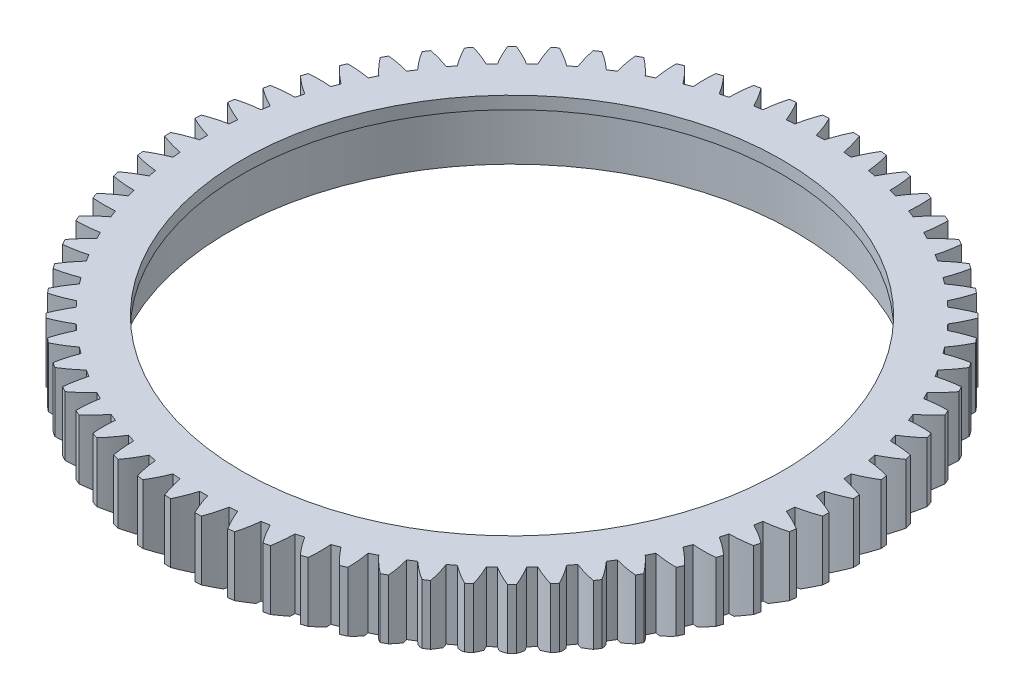
SolidWorks part; units mm, degrees
ref_plane "Front Plane" through (0, 0, 0) normal (0, 0, 1) x (1, 0, 0)
ref_plane "Top Plane" through (0, 0, 0) normal (0, 1, 0) x (1, 0, 0)
ref_plane "Right Plane" through (0, 0, 0) normal (1, 0, 0) x (0, 0, -1)
sketch "Sketch1" plane through (0, 0, 0) normal (0, 1, 0) x (1, 0, 0)
  circle A0 centre (0, 0) radius 53
  circle A1 centre (0, 0) radius 43
  dimension "D1" = 106
  dimension "D2" = 86
extrude "Boss-Extrude1" add sketch "Sketch1" along normal blind 11
sketch "Sketch3" plane through (0, 0, 0) normal (0, -1, 0) x (1, 0, 0)
  circle A0 centre (0, 0) radius 45.1
  dimension "D1" = 90.2
extrude "Cut-Extrude2" cut sketch "Sketch3" against normal blind 9
sketch "Sketch4" plane through (0, 0, 0) normal (0, -1, 0) x (1, 0, 0)
  arc A0 (-52.4646, 1.9286) -> (-49.1199, 0.6319) centre (-43.4466, 20.2271) ccw
  arc A1 (-49.1199, 0.6319) -> (-49.1199, -0.6319) centre (0, 0) ccw
  arc A2 (-49.1199, -0.6319) -> (-52.4646, -1.9286) centre (-43.4466, -20.2271) ccw
  arc A3 (-52.4646, -1.9286) -> (-52.4187, -2.9204) centre (0, 0) ccw
  arc A4 (-52.4187, -2.9204) -> (-48.9687, -3.903) centre (-45.1276, 16.1321) ccw
  arc A5 (-48.9687, -3.903) -> (-48.8521, -5.1614) centre (0, 0) ccw
  arc A6 (-48.8521, -5.1614) -> (-52.0628, -6.7612) centre (-41.3949, -24.1496) ccw
  arc A7 (-52.0628, -6.7612) -> (-51.9256, -7.7446) centre (0, 0) ccw
  arc A8 (-51.9256, -7.7446) -> (-48.3997, -8.4046) centre (-46.4235, 11.8994) ccw
  arc A9 (-48.3997, -8.4046) -> (-48.1675, -9.6469) centre (0, 0) ccw
  arc A10 (-48.1675, -9.6469) -> (-51.2169, -11.5361) centre (-38.9901, -27.866) ccw
  arc A11 (-51.2169, -11.5361) -> (-50.9896, -12.5026) centre (0, 0) ccw
  arc A12 (-50.9896, -12.5026) -> (-47.4177, -12.8345) centre (-47.3234, 7.5653) ccw
  arc A13 (-47.4177, -12.8345) -> (-47.0719, -14.0501) centre (0, 0) ccw
  arc A14 (-47.0719, -14.0501) -> (-49.934, -16.2126) centre (-36.2526, -31.3447) ccw
  arc A15 (-49.934, -16.2126) -> (-49.6184, -17.154) centre (0, 0) ccw
  arc A16 (-49.6184, -17.154) -> (-46.0312, -17.1549) centre (-47.8196, 3.1665) ccw
  arc A17 (-46.0312, -17.1549) -> (-45.5747, -18.3334) centre (0, 0) ccw
  arc A18 (-45.5747, -18.3334) -> (-48.2251, -20.7508) centre (-33.2058, -34.5559) ccw
  arc A19 (-48.2251, -20.7508) -> (-47.824, -21.659) centre (0, 0) ccw
  arc A20 (-47.824, -21.659) -> (-44.252, -21.329) centre (-47.9078, -1.2592) ccw
  arc A21 (-44.252, -21.329) -> (-43.6887, -22.4603) centre (0, 0) ccw
  arc A22 (-43.6887, -22.4603) -> (-46.1047, -25.1119) centre (-29.8758, -37.4724) ccw
  arc A23 (-46.1047, -25.1119) -> (-45.6216, -25.9793) centre (0, 0) ccw
  arc A24 (-45.6216, -25.9793) -> (-42.0953, -25.3211) centre (-47.5872, -5.6742) ccw
  arc A25 (-42.0953, -25.3211) -> (-41.43, -26.3956) centre (0, 0) ccw
  arc A26 (-41.43, -26.3956) -> (-43.591, -29.2588) centre (-26.2908, -40.0691) ccw
  arc A27 (-43.591, -29.2588) -> (-43.0299, -30.0779) centre (0, 0) ccw
  arc A28 (-43.0299, -30.0779) -> (-39.5794, -29.0971) centre (-46.8607, -10.0408) ccw
  arc A29 (-39.5794, -29.0971) -> (-38.8178, -30.1056) centre (0, 0) ccw
  arc A30 (-38.8178, -30.1056) -> (-40.7054, -33.156) centre (-22.4815, -42.324) ccw
  arc A31 (-40.7054, -33.156) -> (-40.0711, -33.9199) centre (0, 0) ccw
  arc A32 (-40.0711, -33.9199) -> (-36.7258, -32.6249) centre (-45.7343, -14.3217) ccw
  arc A33 (-36.7258, -32.6249) -> (-35.8744, -33.5589) centre (0, 0) ccw
  arc A34 (-35.8744, -33.5589) -> (-37.4725, -36.7704) centre (-18.4805, -44.2178) ccw
  arc A35 (-37.4725, -36.7704) -> (-36.7704, -37.4725) centre (0, 0) ccw
  arc A36 (-36.7704, -37.4725) -> (-33.5589, -35.8744) centre (-44.2178, -18.4805) ccw
  arc A37 (-33.5589, -35.8744) -> (-32.6249, -36.7258) centre (0, 0) ccw
  arc A38 (-32.6249, -36.7258) -> (-33.9199, -40.0711) centre (-14.3217, -45.7343) ccw
  arc A39 (-33.9199, -40.0711) -> (-33.156, -40.7054) centre (0, 0) ccw
  arc A40 (-33.156, -40.7054) -> (-30.1056, -38.8178) centre (-42.324, -22.4815) ccw
  arc A41 (-30.1056, -38.8178) -> (-29.0971, -39.5794) centre (0, 0) ccw
  arc A42 (-29.0971, -39.5794) -> (-30.0779, -43.0299) centre (-10.0408, -46.8607) ccw
  arc A43 (-30.0779, -43.0299) -> (-29.2588, -43.591) centre (0, 0) ccw
  arc A44 (-29.2588, -43.591) -> (-26.3956, -41.43) centre (-40.0691, -26.2908) ccw
  arc A45 (-26.3956, -41.43) -> (-25.3211, -42.0953) centre (0, 0) ccw
  arc A46 (-25.3211, -42.0953) -> (-25.9793, -45.6216) centre (-5.6742, -47.5872) ccw
  arc A47 (-25.9793, -45.6216) -> (-25.1119, -46.1047) centre (0, 0) ccw
  arc A48 (-25.1119, -46.1047) -> (-22.4603, -43.6887) centre (-37.4724, -29.8758) ccw
  arc A49 (-22.4603, -43.6887) -> (-21.329, -44.252) centre (0, 0) ccw
  arc A50 (-21.329, -44.252) -> (-21.659, -47.824) centre (-1.2592, -47.9078) ccw
  arc A51 (-21.659, -47.824) -> (-20.7508, -48.2251) centre (0, 0) ccw
  arc A52 (-20.7508, -48.2251) -> (-18.3334, -45.5747) centre (-34.5559, -33.2058) ccw
  arc A53 (-18.3334, -45.5747) -> (-17.1549, -46.0312) centre (0, 0) ccw
  arc A54 (-17.1549, -46.0312) -> (-17.154, -49.6184) centre (3.1665, -47.8196) ccw
  arc A55 (-17.154, -49.6184) -> (-16.2126, -49.934) centre (0, 0) ccw
  arc A56 (-16.2126, -49.934) -> (-14.0501, -47.0719) centre (-31.3447, -36.2526) ccw
  arc A57 (-14.0501, -47.0719) -> (-12.8345, -47.4177) centre (0, 0) ccw
  arc A58 (-12.8345, -47.4177) -> (-12.5026, -50.9896) centre (7.5653, -47.3234) ccw
  arc A59 (-12.5026, -50.9896) -> (-11.5361, -51.2169) centre (0, 0) ccw
  arc A60 (-11.5361, -51.2169) -> (-9.6469, -48.1675) centre (-27.866, -38.9901) ccw
  arc A61 (-9.6469, -48.1675) -> (-8.4046, -48.3997) centre (0, 0) ccw
  arc A62 (-8.4046, -48.3997) -> (-7.7446, -51.9256) centre (11.8994, -46.4235) ccw
  arc A63 (-7.7446, -51.9256) -> (-6.7612, -52.0628) centre (0, 0) ccw
  arc A64 (-6.7612, -52.0628) -> (-5.1614, -48.8521) centre (-24.1496, -41.3949) ccw
  arc A65 (-5.1614, -48.8521) -> (-3.903, -48.9687) centre (0, 0) ccw
  arc A66 (-3.903, -48.9687) -> (-2.9204, -52.4187) centre (16.1321, -45.1276) ccw
  arc A67 (-2.9204, -52.4187) -> (-1.9286, -52.4646) centre (0, 0) ccw
  arc A68 (-1.9286, -52.4646) -> (-0.6319, -49.1199) centre (-20.2271, -43.4466) ccw
  arc A69 (-0.6319, -49.1199) -> (0.6319, -49.1199) centre (0, 0) ccw
  arc A70 (0.6319, -49.1199) -> (1.9286, -52.4646) centre (20.2271, -43.4466) ccw
  arc A71 (1.9286, -52.4646) -> (2.9204, -52.4187) centre (0, 0) ccw
  arc A72 (2.9204, -52.4187) -> (3.903, -48.9687) centre (-16.1321, -45.1276) ccw
  arc A73 (3.903, -48.9687) -> (5.1614, -48.8521) centre (0, 0) ccw
  arc A74 (5.1614, -48.8521) -> (6.7612, -52.0628) centre (24.1496, -41.3949) ccw
  arc A75 (6.7612, -52.0628) -> (7.7446, -51.9256) centre (0, 0) ccw
  arc A76 (7.7446, -51.9256) -> (8.4046, -48.3997) centre (-11.8994, -46.4235) ccw
  arc A77 (8.4046, -48.3997) -> (9.6469, -48.1675) centre (0, 0) ccw
  arc A78 (9.6469, -48.1675) -> (11.5361, -51.2169) centre (27.866, -38.9901) ccw
  arc A79 (11.5361, -51.2169) -> (12.5026, -50.9896) centre (0, 0) ccw
  arc A80 (12.5026, -50.9896) -> (12.8345, -47.4177) centre (-7.5653, -47.3234) ccw
  arc A81 (12.8345, -47.4177) -> (14.0501, -47.0719) centre (0, 0) ccw
  arc A82 (14.0501, -47.0719) -> (16.2126, -49.934) centre (31.3447, -36.2526) ccw
  arc A83 (16.2126, -49.934) -> (17.154, -49.6184) centre (0, 0) ccw
  arc A84 (17.154, -49.6184) -> (17.1549, -46.0312) centre (-3.1665, -47.8196) ccw
  arc A85 (17.1549, -46.0312) -> (18.3334, -45.5747) centre (0, 0) ccw
  arc A86 (18.3334, -45.5747) -> (20.7508, -48.2251) centre (34.5559, -33.2058) ccw
  arc A87 (20.7508, -48.2251) -> (21.659, -47.824) centre (0, 0) ccw
  arc A88 (21.659, -47.824) -> (21.329, -44.252) centre (1.2592, -47.9078) ccw
  arc A89 (21.329, -44.252) -> (22.4603, -43.6887) centre (0, 0) ccw
  arc A90 (22.4603, -43.6887) -> (25.1119, -46.1047) centre (37.4724, -29.8758) ccw
  arc A91 (25.1119, -46.1047) -> (25.9793, -45.6216) centre (0, 0) ccw
  arc A92 (25.9793, -45.6216) -> (25.3211, -42.0953) centre (5.6742, -47.5872) ccw
  arc A93 (25.3211, -42.0953) -> (26.3956, -41.43) centre (0, 0) ccw
  arc A94 (26.3956, -41.43) -> (29.2588, -43.591) centre (40.0691, -26.2908) ccw
  arc A95 (29.2588, -43.591) -> (30.0779, -43.0299) centre (0, 0) ccw
  arc A96 (30.0779, -43.0299) -> (29.0971, -39.5794) centre (10.0408, -46.8607) ccw
  arc A97 (29.0971, -39.5794) -> (30.1056, -38.8178) centre (0, 0) ccw
  arc A98 (30.1056, -38.8178) -> (33.156, -40.7054) centre (42.324, -22.4815) ccw
  arc A99 (33.156, -40.7054) -> (33.9199, -40.0711) centre (0, 0) ccw
  arc A100 (33.9199, -40.0711) -> (32.6249, -36.7258) centre (14.3217, -45.7343) ccw
  arc A101 (32.6249, -36.7258) -> (33.5589, -35.8744) centre (0, 0) ccw
  arc A102 (33.5589, -35.8744) -> (36.7704, -37.4725) centre (44.2178, -18.4805) ccw
  arc A103 (36.7704, -37.4725) -> (37.4725, -36.7704) centre (0, 0) ccw
  arc A104 (37.4725, -36.7704) -> (35.8744, -33.5589) centre (18.4805, -44.2178) ccw
  arc A105 (35.8744, -33.5589) -> (36.7258, -32.6249) centre (0, 0) ccw
  arc A106 (36.7258, -32.6249) -> (40.0711, -33.9199) centre (45.7343, -14.3217) ccw
  arc A107 (40.0711, -33.9199) -> (40.7054, -33.156) centre (0, 0) ccw
  arc A108 (40.7054, -33.156) -> (38.8178, -30.1056) centre (22.4815, -42.324) ccw
  arc A109 (38.8178, -30.1056) -> (39.5794, -29.0971) centre (0, 0) ccw
  arc A110 (39.5794, -29.0971) -> (43.0299, -30.0779) centre (46.8607, -10.0408) ccw
  arc A111 (43.0299, -30.0779) -> (43.591, -29.2588) centre (0, 0) ccw
  arc A112 (43.591, -29.2588) -> (41.43, -26.3956) centre (26.2908, -40.0691) ccw
  arc A113 (41.43, -26.3956) -> (42.0953, -25.3211) centre (0, 0) ccw
  arc A114 (42.0953, -25.3211) -> (45.6216, -25.9793) centre (47.5872, -5.6742) ccw
  arc A115 (45.6216, -25.9793) -> (46.1047, -25.1119) centre (0, 0) ccw
  arc A116 (46.1047, -25.1119) -> (43.6887, -22.4603) centre (29.8758, -37.4724) ccw
  arc A117 (43.6887, -22.4603) -> (44.252, -21.329) centre (0, 0) ccw
  arc A118 (44.252, -21.329) -> (47.824, -21.659) centre (47.9078, -1.2592) ccw
  arc A119 (47.824, -21.659) -> (48.2251, -20.7508) centre (0, 0) ccw
  arc A120 (48.2251, -20.7508) -> (45.5747, -18.3334) centre (33.2058, -34.5559) ccw
  arc A121 (45.5747, -18.3334) -> (46.0312, -17.1549) centre (0, 0) ccw
  arc A122 (46.0312, -17.1549) -> (49.6184, -17.154) centre (47.8196, 3.1665) ccw
  arc A123 (49.6184, -17.154) -> (49.934, -16.2126) centre (0, 0) ccw
  arc A124 (49.934, -16.2126) -> (47.0719, -14.0501) centre (36.2526, -31.3447) ccw
  arc A125 (47.0719, -14.0501) -> (47.4177, -12.8345) centre (0, 0) ccw
  arc A126 (47.4177, -12.8345) -> (50.9896, -12.5026) centre (47.3234, 7.5653) ccw
  arc A127 (50.9896, -12.5026) -> (51.2169, -11.5361) centre (0, 0) ccw
  arc A128 (51.2169, -11.5361) -> (48.1675, -9.6469) centre (38.9901, -27.866) ccw
  arc A129 (48.1675, -9.6469) -> (48.3997, -8.4046) centre (0, 0) ccw
  arc A130 (48.3997, -8.4046) -> (51.9256, -7.7446) centre (46.4235, 11.8994) ccw
  arc A131 (51.9256, -7.7446) -> (52.0628, -6.7612) centre (0, 0) ccw
  arc A132 (52.0628, -6.7612) -> (48.8521, -5.1614) centre (41.3949, -24.1496) ccw
  arc A133 (48.8521, -5.1614) -> (48.9687, -3.903) centre (0, 0) ccw
  arc A134 (48.9687, -3.903) -> (52.4187, -2.9204) centre (45.1276, 16.1321) ccw
  arc A135 (52.4187, -2.9204) -> (52.4646, -1.9286) centre (0, 0) ccw
  arc A136 (52.4646, -1.9286) -> (49.1199, -0.6319) centre (43.4466, -20.2271) ccw
  arc A137 (49.1199, -0.6319) -> (49.1199, 0.6319) centre (0, 0) ccw
  arc A138 (49.1199, 0.6319) -> (52.4646, 1.9286) centre (43.4466, 20.2271) ccw
  arc A139 (52.4646, 1.9286) -> (52.4187, 2.9204) centre (0, 0) ccw
  arc A140 (52.4187, 2.9204) -> (48.9687, 3.903) centre (45.1276, -16.1321) ccw
  arc A141 (48.9687, 3.903) -> (48.8521, 5.1614) centre (0, 0) ccw
  arc A142 (48.8521, 5.1614) -> (52.0628, 6.7612) centre (41.3949, 24.1496) ccw
  arc A143 (52.0628, 6.7612) -> (51.9256, 7.7446) centre (0, 0) ccw
  arc A144 (51.9256, 7.7446) -> (48.3997, 8.4046) centre (46.4235, -11.8994) ccw
  arc A145 (48.3997, 8.4046) -> (48.1675, 9.6469) centre (0, 0) ccw
  arc A146 (48.1675, 9.6469) -> (51.2169, 11.5361) centre (38.9901, 27.866) ccw
  arc A147 (51.2169, 11.5361) -> (50.9896, 12.5026) centre (0, 0) ccw
  arc A148 (50.9896, 12.5026) -> (47.4177, 12.8345) centre (47.3234, -7.5653) ccw
  arc A149 (47.4177, 12.8345) -> (47.0719, 14.0501) centre (0, 0) ccw
  arc A150 (47.0719, 14.0501) -> (49.934, 16.2126) centre (36.2526, 31.3447) ccw
  arc A151 (49.934, 16.2126) -> (49.6184, 17.154) centre (0, 0) ccw
  arc A152 (49.6184, 17.154) -> (46.0312, 17.1549) centre (47.8196, -3.1665) ccw
  arc A153 (46.0312, 17.1549) -> (45.5747, 18.3334) centre (0, 0) ccw
  arc A154 (45.5747, 18.3334) -> (48.2251, 20.7508) centre (33.2058, 34.5559) ccw
  arc A155 (48.2251, 20.7508) -> (47.824, 21.659) centre (0, 0) ccw
  arc A156 (47.824, 21.659) -> (44.252, 21.329) centre (47.9078, 1.2592) ccw
  arc A157 (44.252, 21.329) -> (43.6887, 22.4603) centre (0, 0) ccw
  arc A158 (43.6887, 22.4603) -> (46.1047, 25.1119) centre (29.8758, 37.4724) ccw
  arc A159 (46.1047, 25.1119) -> (45.6216, 25.9793) centre (0, 0) ccw
  arc A160 (45.6216, 25.9793) -> (42.0953, 25.3211) centre (47.5872, 5.6742) ccw
  arc A161 (42.0953, 25.3211) -> (41.43, 26.3956) centre (0, 0) ccw
  arc A162 (41.43, 26.3956) -> (43.591, 29.2588) centre (26.2908, 40.0691) ccw
  arc A163 (43.591, 29.2588) -> (43.0299, 30.0779) centre (0, 0) ccw
  arc A164 (43.0299, 30.0779) -> (39.5794, 29.0971) centre (46.8607, 10.0408) ccw
  arc A165 (39.5794, 29.0971) -> (38.8178, 30.1056) centre (0, 0) ccw
  arc A166 (38.8178, 30.1056) -> (40.7054, 33.156) centre (22.4815, 42.324) ccw
  arc A167 (40.7054, 33.156) -> (40.0711, 33.9199) centre (0, 0) ccw
  arc A168 (40.0711, 33.9199) -> (36.7258, 32.6249) centre (45.7343, 14.3217) ccw
  arc A169 (36.7258, 32.6249) -> (35.8744, 33.5589) centre (0, 0) ccw
  arc A170 (35.8744, 33.5589) -> (37.4725, 36.7704) centre (18.4805, 44.2178) ccw
  arc A171 (37.4725, 36.7704) -> (36.7704, 37.4725) centre (0, 0) ccw
  arc A172 (36.7704, 37.4725) -> (33.5589, 35.8744) centre (44.2178, 18.4805) ccw
  arc A173 (33.5589, 35.8744) -> (32.6249, 36.7258) centre (0, 0) ccw
  arc A174 (32.6249, 36.7258) -> (33.9199, 40.0711) centre (14.3217, 45.7343) ccw
  arc A175 (33.9199, 40.0711) -> (33.156, 40.7054) centre (0, 0) ccw
  arc A176 (33.156, 40.7054) -> (30.1056, 38.8178) centre (42.324, 22.4815) ccw
  arc A177 (30.1056, 38.8178) -> (29.0971, 39.5794) centre (0, 0) ccw
  arc A178 (29.0971, 39.5794) -> (30.0779, 43.0299) centre (10.0408, 46.8607) ccw
  arc A179 (30.0779, 43.0299) -> (29.2588, 43.591) centre (0, 0) ccw
  arc A180 (29.2588, 43.591) -> (26.3956, 41.43) centre (40.0691, 26.2908) ccw
  arc A181 (26.3956, 41.43) -> (25.3211, 42.0953) centre (0, 0) ccw
  arc A182 (25.3211, 42.0953) -> (25.9793, 45.6216) centre (5.6742, 47.5872) ccw
  arc A183 (25.9793, 45.6216) -> (25.1119, 46.1047) centre (0, 0) ccw
  arc A184 (25.1119, 46.1047) -> (22.4603, 43.6887) centre (37.4724, 29.8758) ccw
  arc A185 (22.4603, 43.6887) -> (21.329, 44.252) centre (0, 0) ccw
  arc A186 (21.329, 44.252) -> (21.659, 47.824) centre (1.2592, 47.9078) ccw
  arc A187 (21.659, 47.824) -> (20.7508, 48.2251) centre (0, 0) ccw
  arc A188 (20.7508, 48.2251) -> (18.3334, 45.5747) centre (34.5559, 33.2058) ccw
  arc A189 (18.3334, 45.5747) -> (17.1549, 46.0312) centre (0, 0) ccw
  arc A190 (17.1549, 46.0312) -> (17.154, 49.6184) centre (-3.1665, 47.8196) ccw
  arc A191 (17.154, 49.6184) -> (16.2126, 49.934) centre (0, 0) ccw
  arc A192 (16.2126, 49.934) -> (14.0501, 47.0719) centre (31.3447, 36.2526) ccw
  arc A193 (14.0501, 47.0719) -> (12.8345, 47.4177) centre (0, 0) ccw
  arc A194 (12.8345, 47.4177) -> (12.5026, 50.9896) centre (-7.5653, 47.3234) ccw
  arc A195 (12.5026, 50.9896) -> (11.5361, 51.2169) centre (0, 0) ccw
  arc A196 (11.5361, 51.2169) -> (9.6469, 48.1675) centre (27.866, 38.9901) ccw
  arc A197 (9.6469, 48.1675) -> (8.4046, 48.3997) centre (0, 0) ccw
  arc A198 (8.4046, 48.3997) -> (7.7446, 51.9256) centre (-11.8994, 46.4235) ccw
  arc A199 (7.7446, 51.9256) -> (6.7612, 52.0628) centre (0, 0) ccw
  arc A200 (6.7612, 52.0628) -> (5.1614, 48.8521) centre (24.1496, 41.3949) ccw
  arc A201 (5.1614, 48.8521) -> (3.903, 48.9687) centre (0, 0) ccw
  arc A202 (3.903, 48.9687) -> (2.9204, 52.4187) centre (-16.1321, 45.1276) ccw
  arc A203 (2.9204, 52.4187) -> (1.9286, 52.4646) centre (0, 0) ccw
  arc A204 (1.9286, 52.4646) -> (0.6319, 49.1199) centre (20.2271, 43.4466) ccw
  arc A205 (0.6319, 49.1199) -> (-0.6319, 49.1199) centre (0, 0) ccw
  arc A206 (-0.6319, 49.1199) -> (-1.9286, 52.4646) centre (-20.2271, 43.4466) ccw
  arc A207 (-1.9286, 52.4646) -> (-2.9204, 52.4187) centre (0, 0) ccw
  arc A208 (-2.9204, 52.4187) -> (-3.903, 48.9687) centre (16.1321, 45.1276) ccw
  arc A209 (-3.903, 48.9687) -> (-5.1614, 48.8521) centre (0, 0) ccw
  arc A210 (-5.1614, 48.8521) -> (-6.7612, 52.0628) centre (-24.1496, 41.3949) ccw
  arc A211 (-6.7612, 52.0628) -> (-7.7446, 51.9256) centre (0, 0) ccw
  arc A212 (-7.7446, 51.9256) -> (-8.4046, 48.3997) centre (11.8994, 46.4235) ccw
  arc A213 (-8.4046, 48.3997) -> (-9.6469, 48.1675) centre (0, 0) ccw
  arc A214 (-9.6469, 48.1675) -> (-11.5361, 51.2169) centre (-27.866, 38.9901) ccw
  arc A215 (-11.5361, 51.2169) -> (-12.5026, 50.9896) centre (0, 0) ccw
  arc A216 (-12.5026, 50.9896) -> (-12.8345, 47.4177) centre (7.5653, 47.3234) ccw
  arc A217 (-12.8345, 47.4177) -> (-14.0501, 47.0719) centre (0, 0) ccw
  arc A218 (-14.0501, 47.0719) -> (-16.2126, 49.934) centre (-31.3447, 36.2526) ccw
  arc A219 (-16.2126, 49.934) -> (-17.154, 49.6184) centre (0, 0) ccw
  arc A220 (-17.154, 49.6184) -> (-17.1549, 46.0312) centre (3.1665, 47.8196) ccw
  arc A221 (-17.1549, 46.0312) -> (-18.3334, 45.5747) centre (0, 0) ccw
  arc A222 (-18.3334, 45.5747) -> (-20.7508, 48.2251) centre (-34.5559, 33.2058) ccw
  arc A223 (-20.7508, 48.2251) -> (-21.659, 47.824) centre (0, 0) ccw
  arc A224 (-21.659, 47.824) -> (-21.329, 44.252) centre (-1.2592, 47.9078) ccw
  arc A225 (-21.329, 44.252) -> (-22.4603, 43.6887) centre (0, 0) ccw
  arc A226 (-22.4603, 43.6887) -> (-25.1119, 46.1047) centre (-37.4724, 29.8758) ccw
  arc A227 (-25.1119, 46.1047) -> (-25.9793, 45.6216) centre (0, 0) ccw
  arc A228 (-25.9793, 45.6216) -> (-25.3211, 42.0953) centre (-5.6742, 47.5872) ccw
  arc A229 (-25.3211, 42.0953) -> (-26.3956, 41.43) centre (0, 0) ccw
  arc A230 (-26.3956, 41.43) -> (-29.2588, 43.591) centre (-40.0691, 26.2908) ccw
  arc A231 (-29.2588, 43.591) -> (-30.0779, 43.0299) centre (0, 0) ccw
  arc A232 (-30.0779, 43.0299) -> (-29.0971, 39.5794) centre (-10.0408, 46.8607) ccw
  arc A233 (-29.0971, 39.5794) -> (-30.1056, 38.8178) centre (0, 0) ccw
  arc A234 (-30.1056, 38.8178) -> (-33.156, 40.7054) centre (-42.324, 22.4815) ccw
  arc A235 (-33.156, 40.7054) -> (-33.9199, 40.0711) centre (0, 0) ccw
  arc A236 (-33.9199, 40.0711) -> (-32.6249, 36.7258) centre (-14.3217, 45.7343) ccw
  arc A237 (-32.6249, 36.7258) -> (-33.5589, 35.8744) centre (0, 0) ccw
  arc A238 (-33.5589, 35.8744) -> (-36.7704, 37.4725) centre (-44.2178, 18.4805) ccw
  arc A239 (-36.7704, 37.4725) -> (-37.4725, 36.7704) centre (0, 0) ccw
  arc A240 (-37.4725, 36.7704) -> (-35.8744, 33.5589) centre (-18.4805, 44.2178) ccw
  arc A241 (-35.8744, 33.5589) -> (-36.7258, 32.6249) centre (0, 0) ccw
  arc A242 (-36.7258, 32.6249) -> (-40.0711, 33.9199) centre (-45.7343, 14.3217) ccw
  arc A243 (-40.0711, 33.9199) -> (-40.7054, 33.156) centre (0, 0) ccw
  arc A244 (-40.7054, 33.156) -> (-38.8178, 30.1056) centre (-22.4815, 42.324) ccw
  arc A245 (-38.8178, 30.1056) -> (-39.5794, 29.0971) centre (0, 0) ccw
  arc A246 (-39.5794, 29.0971) -> (-43.0299, 30.0779) centre (-46.8607, 10.0408) ccw
  arc A247 (-43.0299, 30.0779) -> (-43.591, 29.2588) centre (0, 0) ccw
  arc A248 (-43.591, 29.2588) -> (-41.43, 26.3956) centre (-26.2908, 40.0691) ccw
  arc A249 (-41.43, 26.3956) -> (-42.0953, 25.3211) centre (0, 0) ccw
  arc A250 (-42.0953, 25.3211) -> (-45.6216, 25.9793) centre (-47.5872, 5.6742) ccw
  arc A251 (-45.6216, 25.9793) -> (-46.1047, 25.1119) centre (0, 0) ccw
  arc A252 (-46.1047, 25.1119) -> (-43.6887, 22.4603) centre (-29.8758, 37.4724) ccw
  arc A253 (-43.6887, 22.4603) -> (-44.252, 21.329) centre (0, 0) ccw
  arc A254 (-44.252, 21.329) -> (-47.824, 21.659) centre (-47.9078, 1.2592) ccw
  arc A255 (-47.824, 21.659) -> (-48.2251, 20.7508) centre (0, 0) ccw
  arc A256 (-48.2251, 20.7508) -> (-45.5747, 18.3334) centre (-33.2058, 34.5559) ccw
  arc A257 (-45.5747, 18.3334) -> (-46.0312, 17.1549) centre (0, 0) ccw
  arc A258 (-46.0312, 17.1549) -> (-49.6184, 17.154) centre (-47.8196, -3.1665) ccw
  arc A259 (-49.6184, 17.154) -> (-49.934, 16.2126) centre (0, 0) ccw
  arc A260 (-49.934, 16.2126) -> (-47.0719, 14.0501) centre (-36.2526, 31.3447) ccw
  arc A261 (-47.0719, 14.0501) -> (-47.4177, 12.8345) centre (0, 0) ccw
  arc A262 (-47.4177, 12.8345) -> (-50.9896, 12.5026) centre (-47.3234, -7.5653) ccw
  arc A263 (-50.9896, 12.5026) -> (-51.2169, 11.5361) centre (0, 0) ccw
  arc A264 (-51.2169, 11.5361) -> (-48.1675, 9.6469) centre (-38.9901, 27.866) ccw
  arc A265 (-48.1675, 9.6469) -> (-48.3997, 8.4046) centre (0, 0) ccw
  arc A266 (-48.3997, 8.4046) -> (-51.9256, 7.7446) centre (-46.4235, -11.8994) ccw
  arc A267 (-51.9256, 7.7446) -> (-52.0628, 6.7612) centre (0, 0) ccw
  arc A268 (-52.0628, 6.7612) -> (-48.8521, 5.1614) centre (-41.3949, 24.1496) ccw
  arc A269 (-48.8521, 5.1614) -> (-48.9687, 3.903) centre (0, 0) ccw
  arc A270 (-48.9687, 3.903) -> (-52.4187, 2.9204) centre (-45.1276, -16.1321) ccw
  arc A271 (-52.4187, 2.9204) -> (-52.4646, 1.9286) centre (0, 0) ccw
  circle A272 centre (0, 0) radius 68.1947
extrude "Cut-Extrude3" cut sketch "Sketch4" against normal blind 43
sketch "Sketch5" plane through (0, 0, 0) normal (1, 0, 0) x (0, 0, -1)
  line L0 (-54.2272, 2.4669) -> (-47.2251, -1.4886)
  line L1 (-47.2251, -1.4886) -> (-54.2272, -2.6305)
  line L2 (-54.2272, -2.6305) -> (-54.2272, 2.4669)
  line L3 (0, 0) -> (0, 15.6014) construction
revolve "Cut-Revolve1" cut sketch "Sketch5" angle 360 about L3
sketch "Sketch7" plane through (0, 0, 0) normal (0, 1, 0) x (1, 0, 0)
  circle A0 centre (0, 0) radius 51 construction
  dimension "D1" = 102
